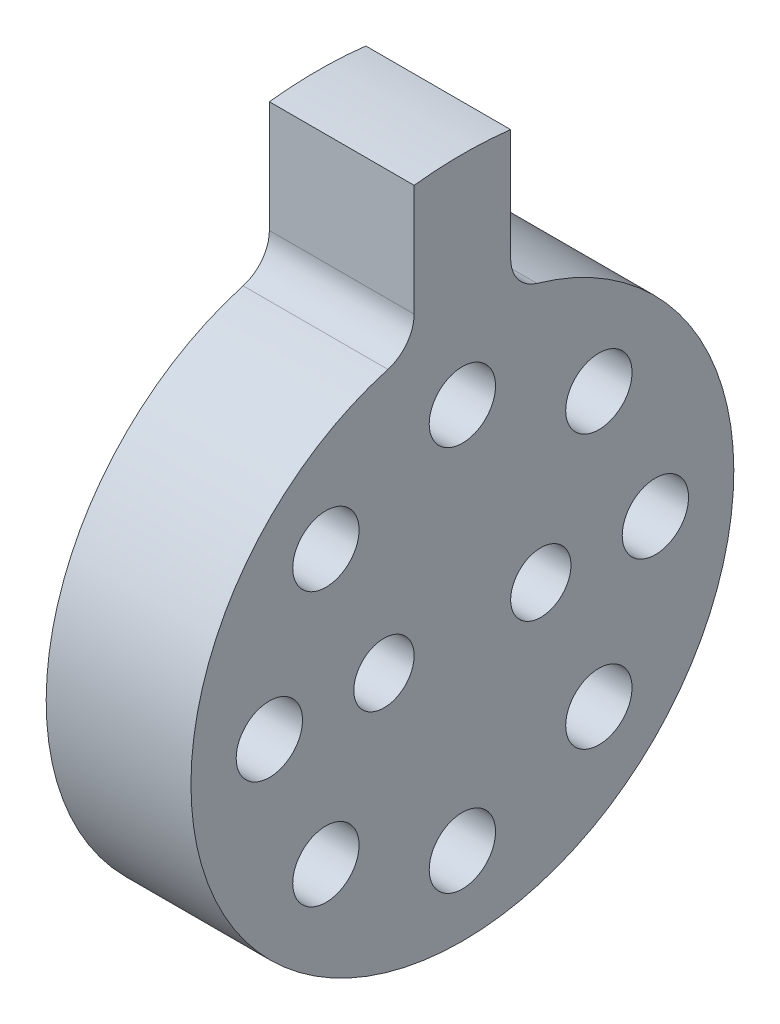
SolidWorks part; units mm, degrees
material "45#"
ref_plane "前视" through (0, 0, 0) normal (0, 0, 1) x (1, 0, 0)
ref_plane "上视" through (0, 0, 0) normal (0, 1, 0) x (1, 0, 0)
ref_plane "右视" through (0, 0, 0) normal (1, 0, 0) x (0, 0, -1)
sketch "草图1" plane through (0, 0, 0) normal (1, 0, 0) x (0, 0, -1)
  circle A0 centre (0, 0) radius 34
  dimension "D1" = 68
extrude "凸台-拉伸1" add sketch "草图1" along normal blind 12
hole_wizard "打孔尺寸根据内六角圆柱头螺钉的类型1" positions "草图3" profile "草图2" counterbore size "M5" standard "Gb" end condition through all
sketch "草图3" plane through (0, 0, 0) normal (-1, 0, 0) x (0, 0, 1)
  point P0 (0, 16)
  dimension "D1" = 16
sketch "草图2" plane through (0, 16, 0) normal (0, 1, 0) x (0, 0, 1)
  line L0 (0, 0) -> (0, 12)
  line L1 (0, 12) -> (2.75, 12)
  line L3 (2.75, 12) -> (2.75, 5.7)
  line L4 (2.75, 5.7) -> (5, 5.7)
  line L5 (5, 5.7) -> (5, 0)
  line L7 (5, 0) -> (0, 0)
  line L11 (0, -6.35) -> (0, 107.95) construction
  dimension "通孔孔直径" = 5.5
  dimension "通孔孔深度" = 12
  dimension "柱形沉头孔直径" = 10
  dimension "柱形沉头孔深度" = 5.7
pattern_circular "阵列(圆周)1" count 8 over 360 about axis through (0, 0, 0) along (1, 0, 0) of "打孔尺寸根据内六角圆柱头螺钉的类型1"
sketch "草图4" plane through (0, 0, 0) normal (-1, 0, 0) x (0, 0, 1)
  line L0 (-4, 33.7639) -> (-4, 22.1416)
  line L1 (0, 0) -> (0, 42.5111) construction
  line L2 (4, 33.7639) -> (4, 22.1416)
  arc A0 (-4, 22.1416) -> (4, 22.1416) centre (0, 0) ccw
  circle A1 centre (0, 0) radius 34 construction
  arc A2 (4, 33.7639) -> (-4, 33.7639) centre (0, 0) ccw
  dimension "D1" = 45
  dimension "D2" = 8
extrude "切除-拉伸2" cut sketch "草图4" against normal through all flip side to cut
hole_wizard "M6 螺纹孔1" positions "草图6" profile "草图5" tap size "M6" standard "Gb" end condition through all
sketch "草图6" plane through (0, 0, 0) normal (-1, 0, 0) x (0, 0, 1)
  line L0 (0, 0) -> (0, 22.9655) construction
  line L1 (0, 0) -> (30.3967, 0) construction
  point P0 (6.5, 0)
  point P11 (-6.5, 0)
  dimension "D1" = 13
cosmetic thread "孔螺蚊线1" parameters "D2"=6
cosmetic thread "孔螺蚊线2" parameters "D2"=6
sketch "草图5" plane through (0, 0, 6.5) normal (0, 1, 0) x (0, 0, 1)
  line L0 (0, 0) -> (0, 12)
  line L1 (0, 12) -> (2.5, 12)
  line L2 (2.5, 12) -> (2.5, 0)
  line L5 (2.5, 0) -> (0, 0)
  line L11 (0, -6.35) -> (0, 107.95) construction
  dimension "通孔螺纹孔钻头直径" = 5
  dimension "通孔螺纹孔钻头深度" = 12
fillet "圆角1" radius 3 2 edges at (6, 22.1416, -4) (6, 22.1416, 4)
